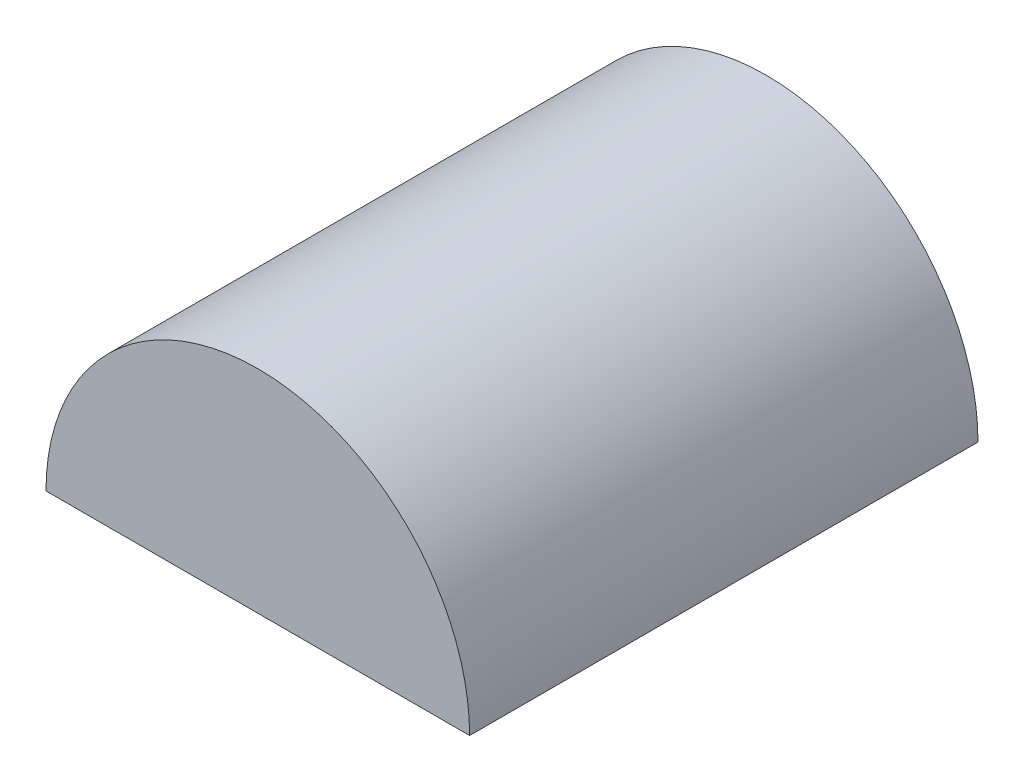
SolidWorks part; units mm, degrees
ref_plane "Front Plane" through (0, 0, 0) normal (0, 0, 1) x (1, 0, 0)
ref_plane "Top Plane" through (0, 0, 0) normal (0, 1, 0) x (1, 0, 0)
ref_plane "Right Plane" through (0, 0, 0) normal (1, 0, 0) x (0, 0, -1)
sketch "Sketch1" plane through (0, 0, 0) normal (0, 0, 1) x (1, 0, 0)
  line L0 (0, 0) -> (-0.25, 0)
  line L1 (0, 0) -> (0.25, 0)
  arc A0 (-0.25, 0) -> (0.25, 0) centre (0, 0) cw
  dimension "D1" = 0.25
extrude "Boss-Extrude1" add sketch "Sketch1" along normal blind 0.6
equation "\"t\"= 0.25'thickness of the sheets"
equation "\"t_cf\"= 0.115'thickness of single carbon fiber layer"
equation "\"t_kapton\"= 0.025'thickness of single Kapton flex layer"
equation "\"t_fr4\"= 0.1'thickness of FR4 with copper layer"
equation "\"joint_flex\"= 0.1'Width of flextures gap"
equation "\"joint_flex_eff\"= 0.02'Width of flecture after castelation"
equation "\"joint_fold\"= 0.2'Width of folding joints for 90deg fold"
equation "\"gap_tolerance\"= 0.002'Width to have interfecence fit between carbon fiber inserts"
equation "\"assemble_angle\"= 90'Angle of assembly parts"
equation "\"link_lift\"= 0.5'Actuation linkage amplification for the lift motion"
equation "\"link_swing\"= 0.45'Actuation linkage amplification for the swing motion"
equation "\"D1@Boss-Extrude1\"=\"joint_fold\""
equation "\"D1@Sketch1\"=\"t\""
